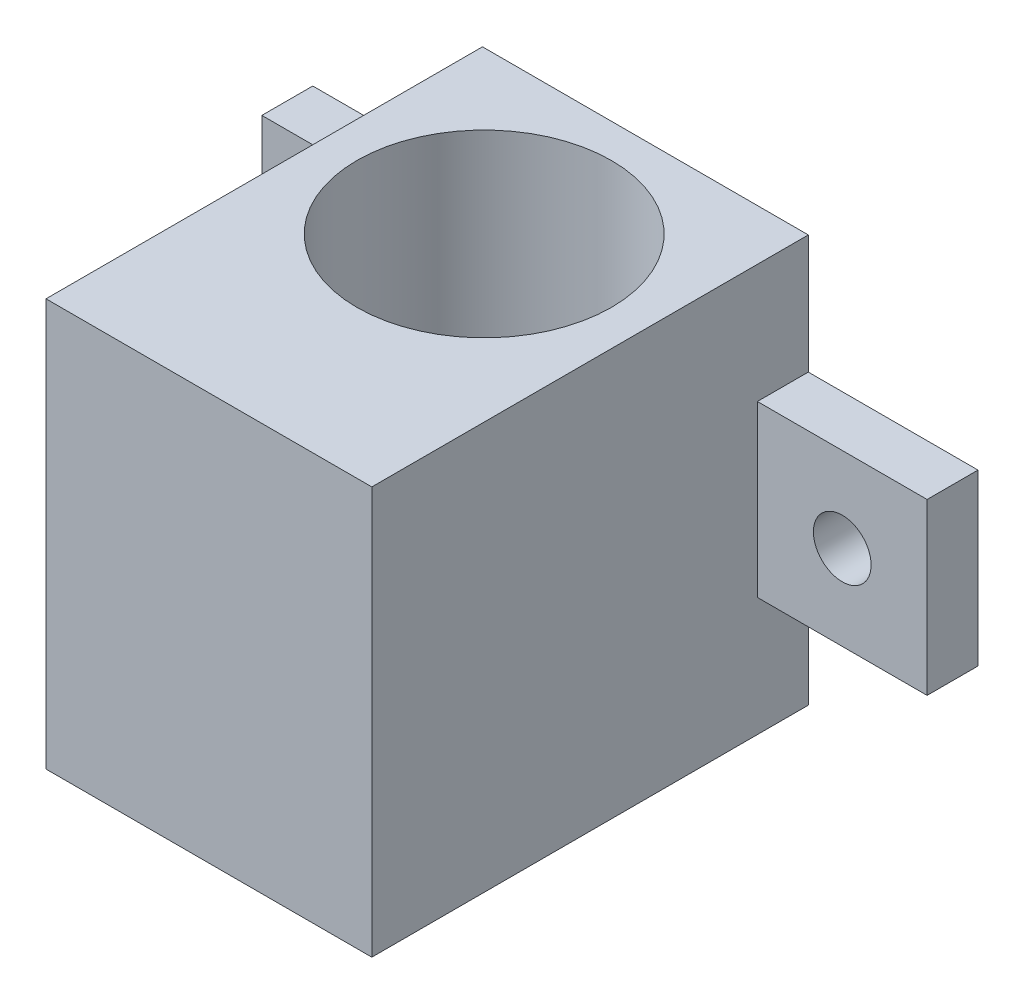
SolidWorks part; units mm, degrees
material "ABS PC"
ref_plane "Front Plane" through (0, 0, 0) normal (0, 0, 1) x (1, 0, 0)
ref_plane "Top Plane" through (0, 0, 0) normal (0, 1, 0) x (1, 0, 0)
ref_plane "Right Plane" through (0, 0, 0) normal (1, 0, 0) x (0, 0, -1)
other "STL Graphics1"
sketch "Sketch2" plane through (0, 0, 0) normal (0, 0, 1) x (1, 0, 0)
  line L0 (-19600, 5000) -> (-9600, 5000)
  line L1 (-9600, 5000) -> (-9600, 12000)
  line L2 (-9600, 12000) -> (9600, 12000)
  line L3 (9600, 12000) -> (9600, 5000)
  line L4 (9600, 5000) -> (19600, 5000)
  line L5 (19600, 5000) -> (19600, -5000)
  line L6 (19600, -5000) -> (9600, -5000)
  line L7 (9600, -5000) -> (9600, -12000)
  line L8 (9600, -12000) -> (-9600, -12000)
  line L9 (-9600, -12000) -> (-9600, -5000)
  line L10 (-9600, -5000) -> (-19600, -5000)
  line L11 (-19600, -5000) -> (-19600, 5000)
  circle A0 centre (-14600, 0) radius 1700
  circle A1 centre (14600, 0) radius 1700
  dimension "D1" = 3400
  dimension "D2" = 3400
  dimension "D3" = 14600
  dimension "D4" = 14600
  dimension "D5" = 24000
  dimension "D6" = 12000
  dimension "D7" = 39200
  dimension "D8" = 19600
  dimension "D9" = 9600
  dimension "D10" = 9600
  dimension "D11" = 5000
  dimension "D12" = 5000
extrude "Boss-Extrude1" add sketch "Sketch2" along normal blind 3000
sketch "Sketch3" plane through (0, 0, 3000) normal (0, 0, 1) x (1, 0, 0)
  line L1 (9600, -12000) -> (-9600, -12000)
  line L2 (9600, -12000) -> (9600, 12000)
  line L3 (9600, 12000) -> (-9600, 12000)
  line L4 (-9600, -12000) -> (-9600, 12000)
extrude "Boss-Extrude2" add sketch "Sketch3" along normal blind 22720
sketch "Sketch4" plane through (0, -12000, 0) normal (0, -1, 0) x (1, 0, 0)
  circle A0 centre (0, 9500) radius 7500
  dimension "D1" = 15000
  dimension "D2" = 9500
extrude "Cut-Extrude1" cut sketch "Sketch4" against normal through all
